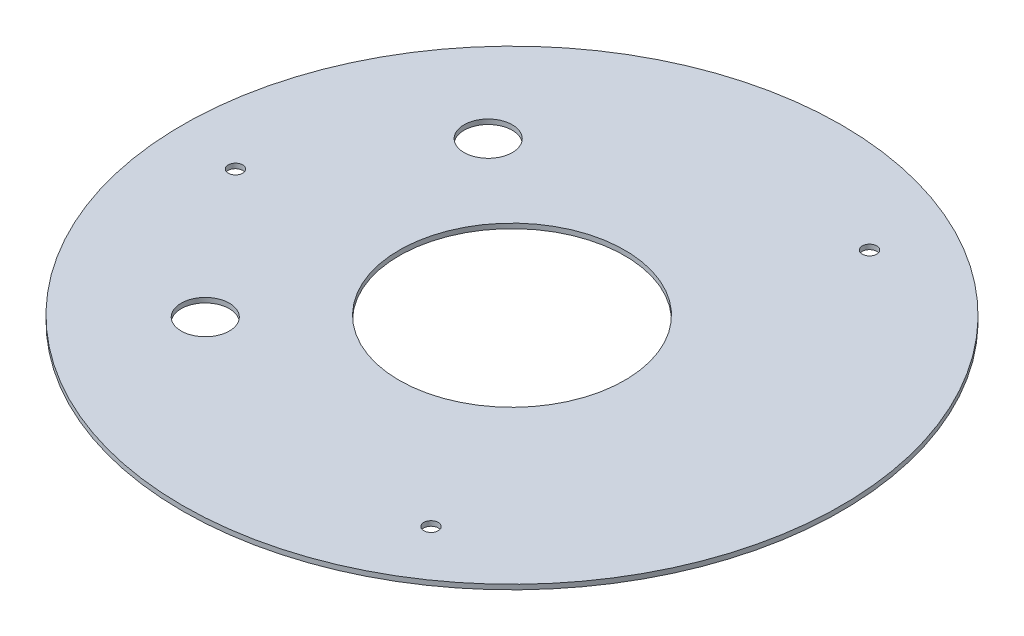
SolidWorks part; units mm, degrees
material "6061 Alloy"
ref_plane "Front Plane" through (0, 0, 0) normal (0, 0, 1) x (1, 0, 0)
ref_plane "Top Plane" through (0, 0, 0) normal (0, 1, 0) x (1, 0, 0)
ref_plane "Right Plane" through (0, 0, 0) normal (1, 0, 0) x (0, 0, -1)
sketch "Sketch1" plane through (0, 0, 0) normal (0, 1, 0) x (-1, 0, 0)
  circle A0 centre (-73.2496, 33.2167) radius 23.401
  circle A1 centre (-73.2496, 33.2167) radius 68.37
extrude "Boss-Extrude1" add sketch "Sketch1" along normal blind 1
sketch "Sketch2" plane through (0, 1, 0) normal (0, -1, 0) x (1, 0, 0)
  circle A0 centre (18.3031, 35.6411) radius 1.5
  circle A1 centre (102.8225, 79.5895) radius 1.5
  circle A2 centre (98.6233, -15.5807) radius 1.5
extrude "Cut-Extrude1" cut sketch "Sketch2" along normal blind 10
sketch "Sketch3" plane through (0, 1, 0) normal (0, 1, 0) x (-1, 0, 0)
  line L0 (-116.9404, -20.8125) -> (-123.2105, -15.0736)
  line L1 (-29.5305, 87.2199) -> (-23.3879, 81.5977)
  line L2 (-26.6402, 84.5744) -> (-120.1073, -17.9139) construction
sketch "Sketch5" plane through (0, 0, 0) normal (0, -1, 0) x (1, 0, 0)
  line L0 (26.9892, 84.1916) -> (120.1073, -17.9139)
  line L1 (26.6402, 84.5744) -> (120.1073, -17.9139) construction
extrude "Cut-Extrude2" cut sketch "Sketch6" against normal blind 10
sketch "Sketch6" plane through (47.342, -2, 109.3589) normal (0, -1, 0) x (0.0976, 0, 0.9952)
  circle A0 centre (-105.7022, -2.0425) radius 5
  circle A1 centre (-44.3242, 1.2553) radius 5
